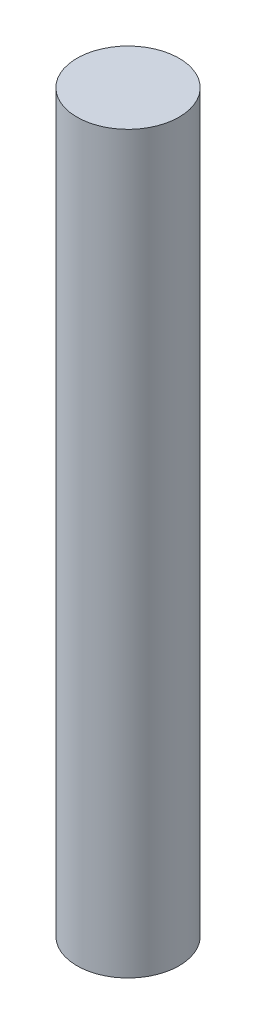
SolidWorks part; units mm, degrees
ref_plane "Plano frontal" through (0, 0, 0) normal (0, 0, 1) x (1, 0, 0)
ref_plane "Plano superior" through (0, 0, 0) normal (0, 1, 0) x (1, 0, 0)
ref_plane "Plano direito" through (0, 0, 0) normal (1, 0, 0) x (0, 0, -1)
sketch "Esboço1" plane through (0, 0, 0) normal (0, 0, 1) x (1, 0, 0)
  line L0 (0, 0) -> (0, 21.6) construction
  line L1 (0, 21.6) -> (1.5, 21.6)
  line L2 (1.5, 21.6) -> (1.5, 0)
  line L3 (1.5, 0) -> (0, 0)
  line L4 (0, 0) -> (0, 21.6)
  dimension "D1" = 1.5
  dimension "D2" = 21.6
revolve "Revolução1" add sketch "Esboço1" angle 360 about L0
